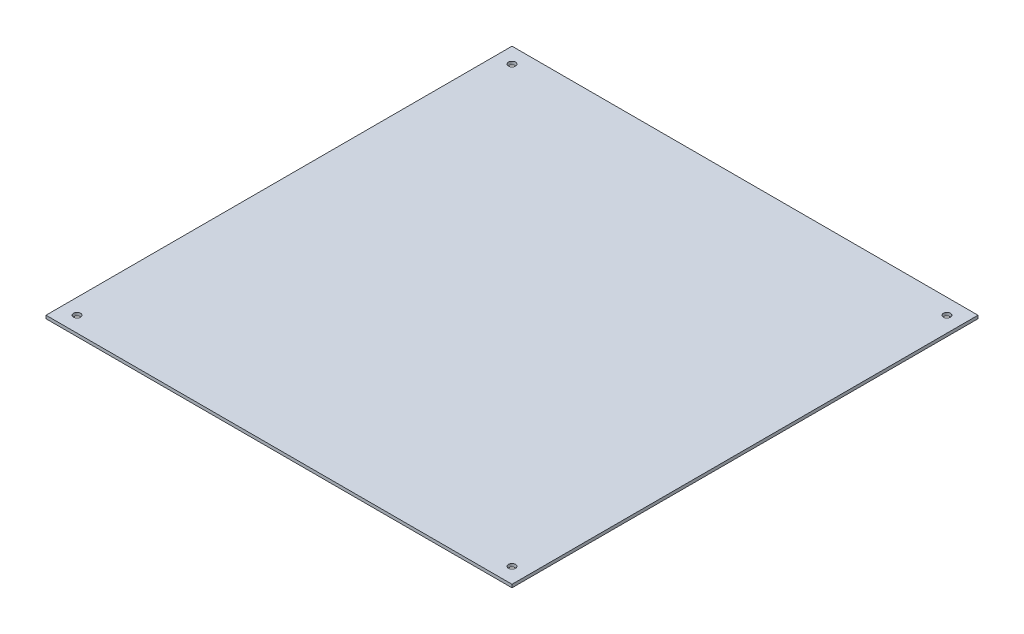
SolidWorks part; units mm, degrees
ref_plane "Front Plane" through (0, 0, 0) normal (0, 0, 1) x (1, 0, 0)
ref_plane "Top Plane" through (0, 0, 0) normal (0, 1, 0) x (1, 0, 0)
ref_plane "Right Plane" through (0, 0, 0) normal (1, 0, 0) x (0, 0, -1)
sketch "Sketch1" plane through (0, 0, 0) normal (0, 1, 0) x (1, 0, 0)
  line L1 (0, 0) -> (600, 0)
  line L2 (0, 0) -> (0, 600)
  line L3 (0, 600) -> (600, 600)
  line L4 (600, 0) -> (600, 600)
  dimension "D1" = 600
  dimension "D2" = 600
extrude "Boss-Extrude1" add sketch "Sketch1" along normal blind 4
sketch "Sketch2" plane through (0, 4, 0) normal (0, 1, 0) x (1, 0, 0)
  line L0 (0, 600) -> (0, 0) construction
  line L2 (600, 600) -> (0, 600) construction
  circle A4 centre (20, 580) radius 4.5
  circle A5 centre (580, 580) radius 4.5
  circle A6 centre (580, 20) radius 4.5
  circle A7 centre (20, 20) radius 4.5
  dimension "D7" = 20
  dimension "D3" = 9
  dimension "D1" = 20
  dimension "D2" = 20
  dimension "D4" = 2
  dimension "D5" = 2
  dimension "D6" = 580
extrude "Cut-Extrude1" cut sketch "Sketch2" against normal up to next
